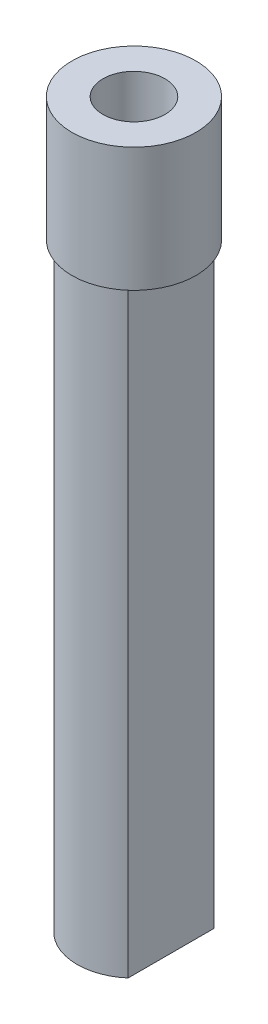
SolidWorks part; units mm, degrees
ref_plane "Front Plane" through (0, 0, 0) normal (0, 0, 1) x (1, 0, 0)
ref_plane "Top Plane" through (0, 0, 0) normal (0, 1, 0) x (1, 0, 0)
ref_plane "Right Plane" through (0, 0, 0) normal (1, 0, 0) x (0, 0, -1)
sketch "Çizim2" plane through (0, 0, 0) normal (0, 1, 0) x (1, 0, 0)
  circle A0 centre (0, 0) radius 3
  dimension "D1" = 6
extrude "Yükseklik-Ekstrüzyon1" add sketch "Çizim2" along normal blind 6
sketch "Çizim3" plane through (0, 6, 0) normal (0, 1, 0) x (1, 0, 0)
  circle A0 centre (0, 0) radius 1.5
  dimension "D1" = 3
extrude "Kes-Ekstrüzyon1" cut sketch "Çizim3" against normal blind 3
sketch "Çizim4" plane through (0, 0, 0) normal (0, -1, 0) x (1, 0, 0)
  line L0 (-1.7989, 2.08) -> (-1.7989, -2.08)
  line L1 (1.7989, 2.08) -> (1.7989, -2.08)
  circle A0 centre (0, 0) radius 2.75
  dimension "D1" = 5.5
  dimension "D2" = 4.16
  dimension "D3" = 4.16
extrude "Yükseklik-Ekstrüzyon2" add sketch "Çizim4" along normal blind 29 contours L1 A0 L0
